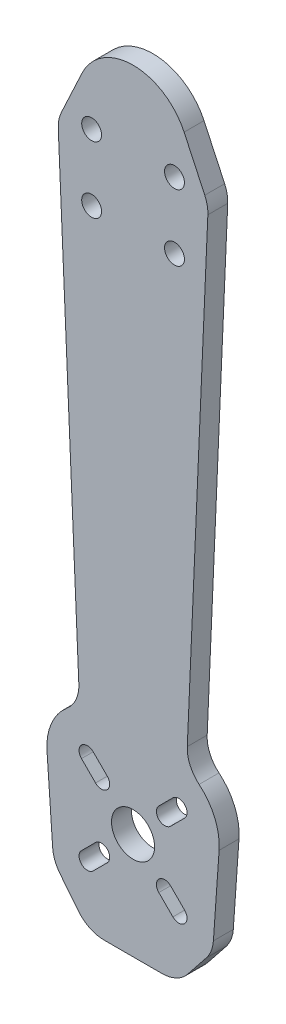
SolidWorks part; units mm, degrees
ref_plane "Alzado" through (0, 0, 0) normal (0, 0, 1) x (1, 0, 0)
ref_plane "Planta" through (0, 0, 0) normal (0, 1, 0) x (1, 0, 0)
ref_plane "Vista lateral" through (0, 0, 0) normal (1, 0, 0) x (0, 0, -1)
ref_plane "Plano1" through (0, 0, 0) normal (0, 0, -1) x (-1, 0, 0)
sketch "Croquis1" plane through (0, 0, 0) normal (0, 0, -1) x (-1, 0, 0)
  line L0 (8.1815, 15.5604) -> (11.2824, 86.5808)
  line L1 (10.8187, 88.912) -> (7.7036, 95.5923)
  line L2 (-7.7036, 95.5923) -> (-10.8187, 88.912)
  line L3 (-11.2824, 86.5808) -> (-8.1815, 15.5604)
  line L4 (-12.9793, 4.4071) -> (-12.1223, -7.8488)
  line L5 (-11.0475, -10.6126) -> (-8.2635, -14.1126)
  line L6 (-4.3504, -16) -> (4.3504, -16)
  line L7 (8.2635, -14.1126) -> (11.0475, -10.6126)
  line L8 (12.1223, -7.8488) -> (12.9793, 4.4071)
  line L9 (7.7782, 6.0104) -> (5.6569, 3.8891)
  line L10 (3.8891, 5.6569) -> (6.0104, 7.7782)
  line L11 (-5.6569, 3.8891) -> (-7.7782, 6.0104)
  line L12 (-6.0104, 7.7782) -> (-3.8891, 5.6569)
  line L13 (-3.8891, -5.6569) -> (-6.0104, -7.7782)
  line L14 (-7.7782, -6.0104) -> (-5.6569, -3.8891)
  line L15 (6.0104, -7.7782) -> (3.8891, -5.6569)
  line L16 (5.6569, -3.8891) -> (7.7782, -6.0104)
  circle A0 centre (0, 0) radius 3.25
  arc A1 (11.2824, 86.5808) -> (10.8187, 88.912) centre (6.2871, 86.7989) ccw
  arc A2 (7.7036, 95.5923) -> (-7.7036, 95.5923) centre (0, 92) ccw
  arc A3 (-10.8187, 88.912) -> (-11.2824, 86.5808) centre (-6.2871, 86.7989) ccw
  arc A4 (-8.1815, 15.5604) -> (-9.9632, 11.5118) centre (-13.1768, 15.3423) cw
  arc A5 (-9.9632, 11.5118) -> (-12.9793, 4.4071) centre (-4.5, 5) ccw
  arc A6 (-12.1223, -7.8488) -> (-11.0475, -10.6126) centre (-7.1345, -7.5) ccw
  arc A7 (-8.2635, -14.1126) -> (-4.3504, -16) centre (-4.3504, -11) ccw
  arc A8 (4.3504, -16) -> (8.2635, -14.1126) centre (4.3504, -11) ccw
  arc A9 (11.0475, -10.6126) -> (12.1223, -7.8488) centre (7.1345, -7.5) ccw
  arc A10 (12.9793, 4.4071) -> (9.9632, 11.5118) centre (4.5, 5) ccw
  arc A11 (9.9632, 11.5118) -> (8.1815, 15.5604) centre (13.1768, 15.3423) cw
  circle A12 centre (6.25, 89) radius 1.5
  circle A13 centre (6.25, 79) radius 1.5
  circle A14 centre (-6.25, 89) radius 1.5
  circle A15 centre (-6.25, 79) radius 1.5
  arc A16 (6.0104, 7.7782) -> (7.7782, 6.0104) centre (6.8943, 6.8943) cw
  arc A17 (5.6569, 3.8891) -> (3.8891, 5.6569) centre (4.773, 4.773) cw
  arc A18 (-7.7782, 6.0104) -> (-6.0104, 7.7782) centre (-6.8943, 6.8943) cw
  arc A19 (-3.8891, 5.6569) -> (-5.6569, 3.8891) centre (-4.773, 4.773) cw
  arc A20 (-5.6569, -3.8891) -> (-3.8891, -5.6569) centre (-4.773, -4.773) cw
  arc A21 (-6.0104, -7.7782) -> (-7.7782, -6.0104) centre (-6.8943, -6.8943) cw
  arc A22 (7.7782, -6.0104) -> (6.0104, -7.7782) centre (6.8943, -6.8943) cw
  arc A23 (3.8891, -5.6569) -> (5.6569, -3.8891) centre (4.773, -4.773) cw
  point P65 (0, 0)
  point P66 (0, 0)
  point P67 (0, 0)
  point P68 (0, 0)
  dimension "D1" = 3
  dimension "D6" = 5
  dimension "D7" = 8.5
  dimension "D8" = 5
  dimension "D9" = 5
  dimension "D10" = 5
  dimension "D11" = 6.5
  dimension "D12" = 1.25
  dimension "D13" = 1.25
  dimension "D16" = 1.25
  dimension "D17" = 1.25
  dimension "D18" = 1.25
  dimension "D19" = 1.25
  dimension "D20" = 1.25
  dimension "D21" = 1.25
  dimension "D22" = 5
  dimension "D23" = 8.5
  dimension "D24" = 8.5
  dimension "D25" = 5
  dimension "D26" = 5
  dimension "D27" = 5
  dimension "D42" = 11
  dimension "D2" = 12.5
  dimension "D3" = 12.5
  dimension "D4" = 10
  dimension "D5" = 10
  dimension "D14" = 3
  dimension "D15" = 3
  dimension "D28" = 79
  dimension "D29" = 92
  dimension "D30" = 9.75
  dimension "D31" = 9.75
  dimension "D32" = 9.75
  dimension "D33" = 9.75
  dimension "D34" = 5
  dimension "D35" = 5
  dimension "D36" = 7.5
  dimension "D37" = 7.5
  dimension "D38" = 4.5
  dimension "D39" = 4.5
  dimension "D40" = 6.25
  dimension "D41" = 6.25
extrude "Saliente-Extruir1" add sketch "Croquis1" against normal blind 3
